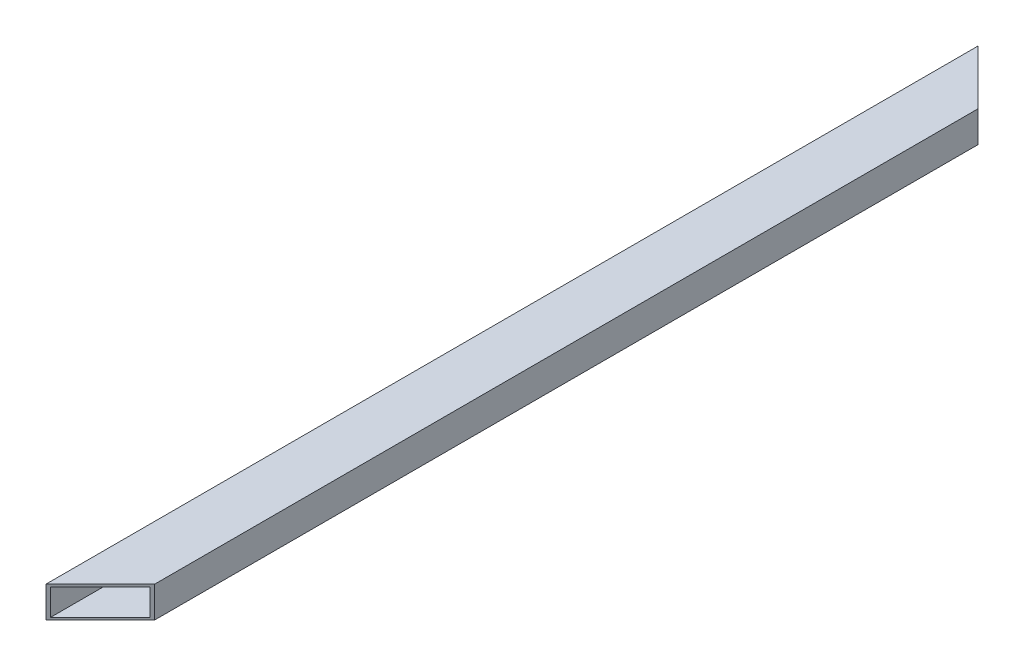
SolidWorks part; units mm, degrees
material "AISI 1045 Acier étiré à froid"
ref_plane "Plan de face" through (0, 0, 0) normal (0, 0, 1) x (1, 0, 0)
ref_plane "Plan de dessus" through (0, 0, 0) normal (0, 1, 0) x (1, 0, 0)
ref_plane "Plan de droite" through (0, 0, 0) normal (1, 0, 0) x (0, 0, -1)
sketch "Esquisse1" plane through (0, 0, 0) normal (0, 0, 1) x (1, 0, 0)
  line L1 (0, 0) -> (35, 0)
  line L2 (0, 0) -> (0, 20)
  line L3 (0, 20) -> (35, 20)
  line L4 (35, 0) -> (35, 20)
  line L5 (1.5, 18.5) -> (33.5, 18.5)
  line L6 (1.5, 18.5) -> (1.5, 1.5)
  line L7 (1.5, 1.5) -> (33.5, 1.5)
  line L8 (33.5, 18.5) -> (33.5, 1.5)
  dimension "D1" = 35
  dimension "D2" = 20
  dimension "D3" = 1.5
  dimension "D4" = 1.5
  dimension "D5" = 1.5
  dimension "D6" = 1.5
extrude "Boss.-Extru.1" add sketch "Esquisse1" along normal blind 600
sketch "Esquisse2" plane through (0, 0, 0) normal (0, 1, 0) x (1, 0, 0)
  line L0 (0, -600) -> (35, -565)
  line L1 (35, -600) -> (35, 0) construction
  line L2 (0, -600) -> (35, -600)
  line L3 (35, -600) -> (35, -565)
  dimension "D1" = 45
extrude "Enlèv. mat.-Extru.1" cut sketch "Esquisse2" along normal through all
sketch "Esquisse4" plane through (0, 0, 0) normal (0, 1, 0) x (1, 0, 0)
  line L0 (0, 0) -> (35, -35)
  line L1 (35, -565) -> (35, 0) construction
  line L2 (35, -35) -> (35, 0)
  line L3 (35, 0) -> (0, 0)
  dimension "D1" = 45
extrude "Enlèv. mat.-Extru.3" cut sketch "Esquisse4" along normal through all
